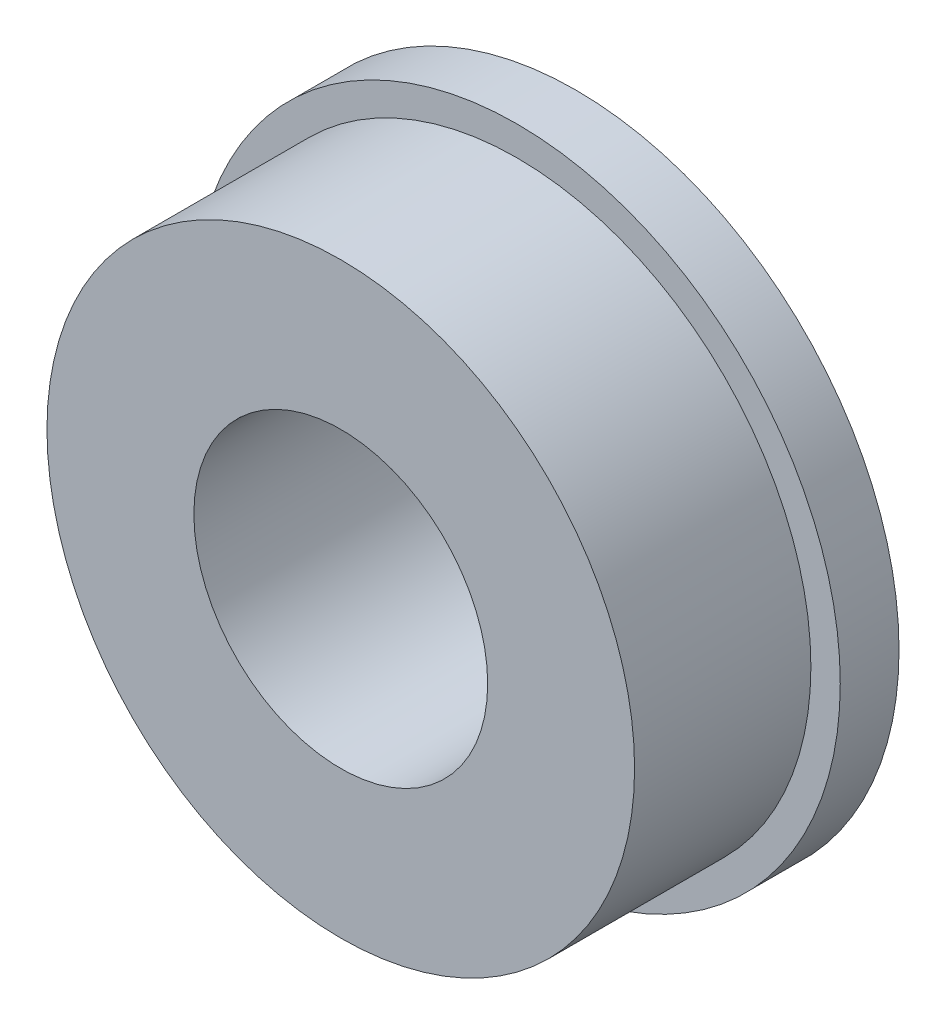
SolidWorks part; units mm, degrees
material "AISI 1035 钢 (SS)"
ref_plane "前视基准面" through (0, 0, 0) normal (0, 0, 1) x (1, 0, 0)
ref_plane "上视基准面" through (0, 0, 0) normal (0, 1, 0) x (1, 0, 0)
ref_plane "右视基准面" through (0, 0, 0) normal (1, 0, 0) x (0, 0, -1)
other "Configuration Table"
sketch "草图1" plane through (0, 0, 0) normal (0, 0, 1) x (1, 0, 0)
  circle A0 centre (0, 0) radius 5
  circle A1 centre (0, 0) radius 2.5
  dimension "D1" = 5
  dimension "D2" = 10
extrude "凸台-拉伸1" add sketch "草图1" along normal blind 3 contours A1 | A0
sketch "草图2" plane through (0, 0, 0) normal (0, 0, -1) x (-1, 0, 0)
  circle A2 centre (0, 0) radius 5.5
  circle A3 centre (0, 0) radius 2.5 construction
  circle A4 centre (0, 0) radius 2.5
  dimension "D1" = 11
extrude "凸台-拉伸2" add sketch "草图2" along normal blind 1 contours A4 | A2
